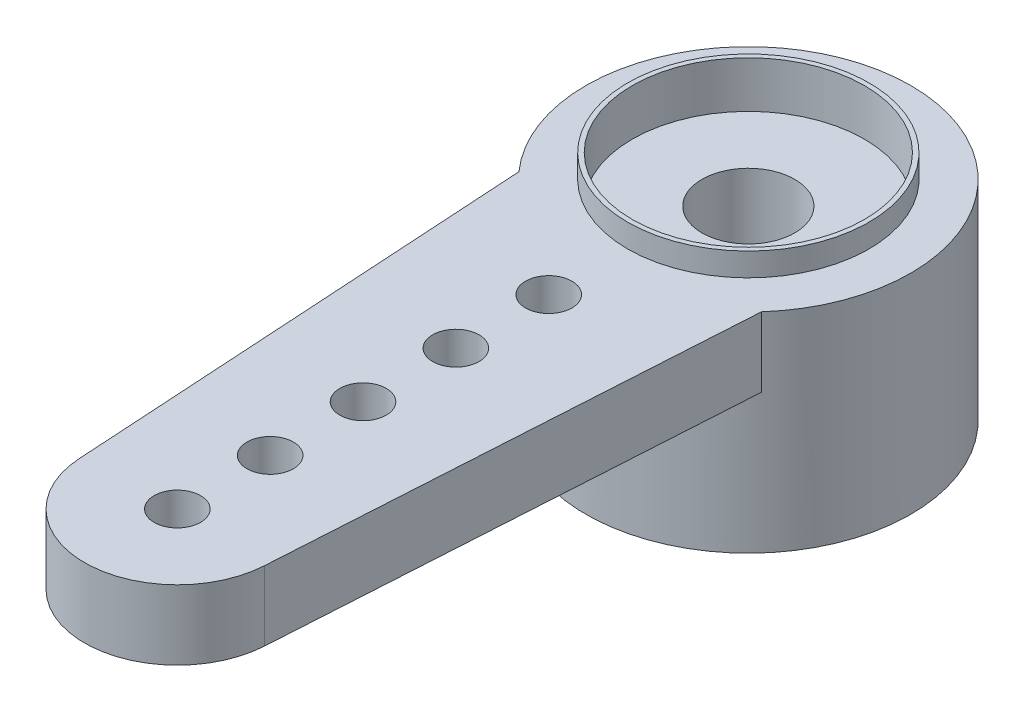
SolidWorks part; units mm, degrees
ref_plane "Front Plane" through (0, 0, 0) normal (0, 0, 1) x (1, 0, 0)
ref_plane "Top Plane" through (0, 0, 0) normal (0, 1, 0) x (1, 0, 0)
ref_plane "Right Plane" through (0, 0, 0) normal (1, 0, 0) x (0, 0, -1)
sketch "Sketch1" plane through (0, 0, 0) normal (0, 1, 0) x (1, 0, 0)
  line L0 (-2.6129, -2.3287) -> (-1.9963, -12.422)
  line L1 (1.9963, -12.422) -> (2.6129, -2.3287)
  line L2 (0, -12.3) -> (0, -10.3) construction
  line L3 (0, -10.3) -> (0, -8.3) construction
  line L4 (0, -8.3) -> (0, -6.3) construction
  line L5 (0, -6.3) -> (0, -4.3) construction
  line L6 (0, -4.3) -> (0, 0) construction
  arc A0 (2.6129, -2.3287) -> (-2.6129, -2.3287) centre (0, 0) ccw
  arc A1 (-1.9963, -12.422) -> (1.9963, -12.422) centre (0, -12.3) ccw
  circle A2 centre (0, 0) radius 2.75 construction
  circle A3 centre (0, -12.3) radius 0.5
  circle A4 centre (0, -10.3) radius 0.5
  circle A5 centre (0, -8.3) radius 0.5
  circle A6 centre (0, -6.3) radius 0.5
  circle A7 centre (0, -4.3) radius 0.5
  circle A8 centre (0, 0) radius 1
  dimension "D1" = 7
  dimension "D2" = 2
  dimension "D3" = 5.5
  dimension "D4" = 17.8
  dimension "D5" = 2
  dimension "D6" = 1
  dimension "D7" = 2
extrude "Boss-Extrude1" add sketch "Sketch1" along normal mid plane 1.5
sketch "Sketch2" plane through (0, -0.75, 0) normal (0, -1, 0) x (1, 0, 0)
  circle A0 centre (0, 0) radius 3.5
  circle A1 centre (0, 0) radius 2.375
  dimension "D1" = 4.75
extrude "Boss-Extrude2" add sketch "Sketch2" along normal blind 3
sketch "Sketch4" plane through (0, 0.75, 0) normal (0, 1, 0) x (1, 0, 0)
  circle A0 centre (0, 0) radius 2.6
  dimension "D1" = 5.2
extrude "Extrude-Thin1" add sketch "Sketch4" along normal blind 0.5 thin thin type one direction reverse wall 0.1
sketch "Sketch5" plane through (0, 0.75, 0) normal (0, 1, 0) x (1, 0, 0)
  circle A0 centre (0, 0) radius 2.5
  circle A1 centre (0, 0) radius 2.5 construction
extrude "Cut-Extrude1" cut sketch "Sketch5" against normal blind 0.5
other "Move Face1" face at (0, -0.75, -2.375) parameters "D1"=0.5
